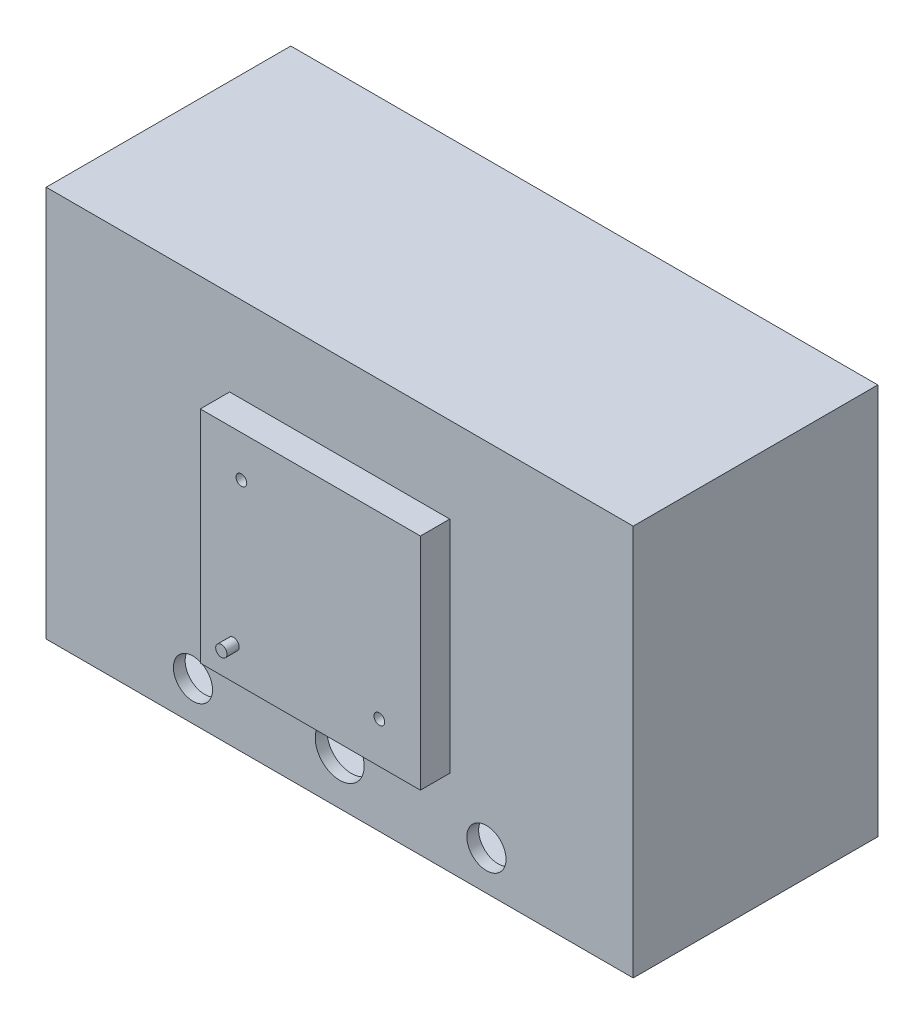
SolidWorks part; units mm, degrees
ref_plane "Front Plane" through (0, 0, 0) normal (0, 0, 1) x (1, 0, 0)
ref_plane "Top Plane" through (0, 0, 0) normal (0, 1, 0) x (1, 0, 0)
ref_plane "Right Plane" through (0, 0, 0) normal (1, 0, 0) x (0, 0, -1)
sketch "Sketch1" plane through (0, 0, 0) normal (0, 0, 1) x (1, 0, 0)
  line L1 (-60, -40) -> (60, -40)
  line L2 (-60, -40) -> (-60, 40)
  line L3 (-60, 40) -> (60, 40)
  line L4 (60, -40) -> (60, 40)
  line L5 (-57.6, -37.6) -> (57.6, -37.6)
  line L6 (-57.6, -37.6) -> (-57.6, 37.6)
  line L7 (-57.6, 37.6) -> (57.6, 37.6)
  line L8 (57.6, -37.6) -> (57.6, 37.6)
extrude "Boss-Extrude1" add sketch "Sketch1" along normal blind 47.6
sketch "Sketch2" plane through (0, 0, 47.6) normal (0, 0, 1) x (1, 0, 0)
  line L1 (-60, -40) -> (60, -40)
  line L2 (-60, -40) -> (-60, 40)
  line L3 (-60, 40) -> (60, 40)
  line L4 (60, -40) -> (60, 40)
extrude "Boss-Extrude2" add sketch "Sketch2" along normal blind 2.4
sketch "Sketch3" plane through (0, 0, 50) normal (0, 0, 1) x (1, 0, 0)
  line L1 (-22.5, -22.5) -> (22.5, -22.5)
  line L2 (-22.5, -22.5) -> (-22.5, 22.5)
  line L3 (-22.5, 22.5) -> (22.5, 22.5)
  line L4 (22.5, -22.5) -> (22.5, 22.5)
extrude "Boss-Extrude3" add sketch "Sketch3" along normal blind 6
sketch "Sketch4" plane through (0, 0, 56) normal (0, 0, 1) x (1, 0, 0)
  circle A0 centre (-14.1, 14.1) radius 1.1
  circle A1 centre (14.1, -14.1) radius 1.1
extrude "Cut-Extrude1" cut sketch "Sketch4" against normal through all
sketch "Sketch5" plane through (0, 0, 56) normal (0, 0, 1) x (1, 0, 0)
  circle A0 centre (-15.7, -15.7) radius 1.15
extrude "Boss-Extrude4" add sketch "Sketch5" along normal blind 2.5
sketch "Sketch6" plane through (0, 0, 50) normal (0, 0, 1) x (1, 0, 0)
  circle A0 centre (-30, -32) radius 4
  circle A1 centre (30, -32) radius 4
  circle A2 centre (0, -30) radius 5
extrude "Cut-Extrude2" cut sketch "Sketch6" against normal blind 3
